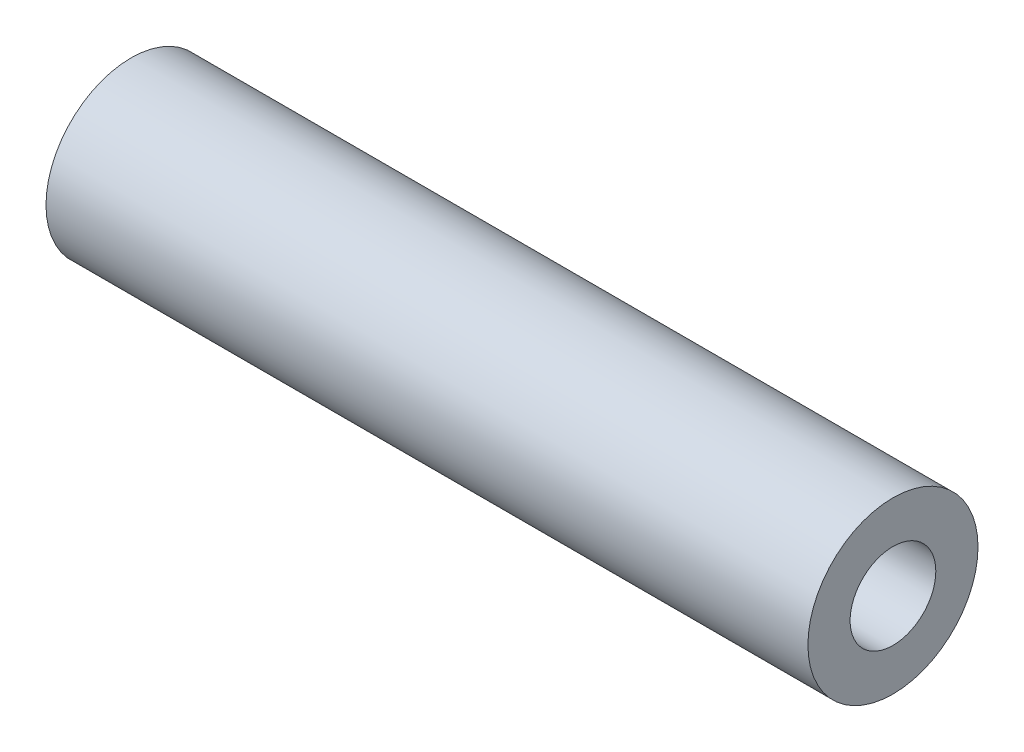
SolidWorks part; units mm, degrees
material "6061-T6 (SS)"
ref_plane "Front Plane" through (0, 0, 0) normal (0, 0, 1) x (1, 0, 0)
ref_plane "Top Plane" through (0, 0, 0) normal (0, 1, 0) x (1, 0, 0)
ref_plane "Right Plane" through (0, 0, 0) normal (1, 0, 0) x (0, 0, -1)
sketch "Sketch1" plane through (0, 0, 0) normal (1, 0, 0) x (0, 0, -1)
  circle A0 centre (0, 0) radius 3.175
  circle A1 centre (0, 0) radius 1.6002
  dimension "D1" = 3.2004
  dimension "D2" = 6.35
extrude "Boss-Extrude1" add sketch "Sketch1" along normal blind 28.448
